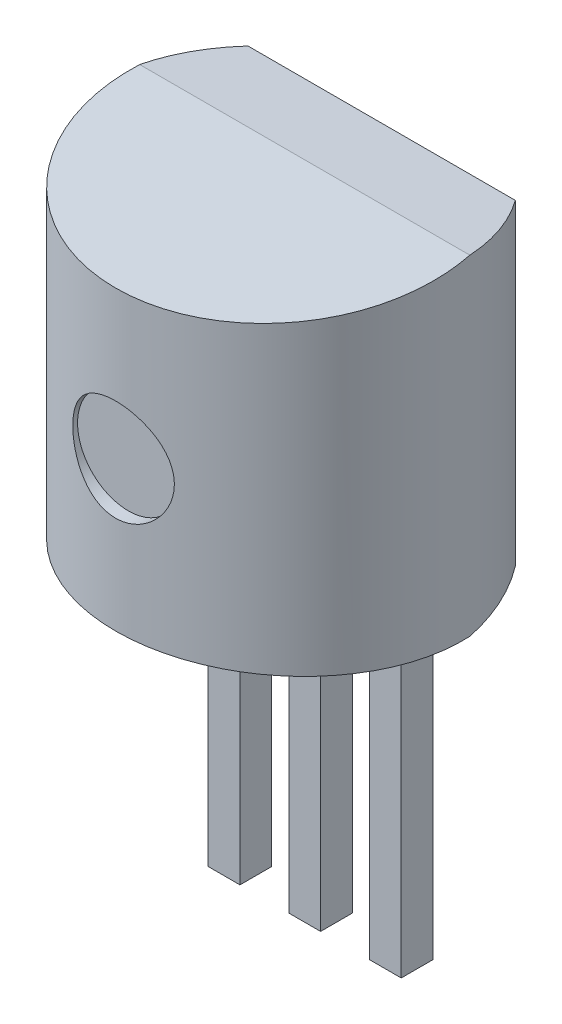
SolidWorks part; units mm, degrees
ref_plane "Front Plane" through (0, 0, 0) normal (0, 0, 1) x (1, 0, 0)
ref_plane "Top Plane" through (0, 0, 0) normal (0, 1, 0) x (1, 0, 0)
ref_plane "Right Plane" through (0, 0, 0) normal (1, 0, 0) x (0, 0, -1)
sketch "Sketch2" plane through (0, 0, 0) normal (0, 1, 0) x (1, 0, 0)
  line L0 (-2.6, 0) -> (2.6, 0) construction
  line L1 (-2.1054, 1.212) -> (2.1054, 1.212)
  line L2 (0, 0) -> (0, 1.212) construction
  arc A0 (-2.1054, 1.212) -> (2.1054, 1.212) centre (0, -0.354) ccw
  point P3 (0, 0)
  dimension "D1" = 4.19
  dimension "D2" = 5.2
  dimension "D3" = 2.27
extrude "Boss-Extrude1" add sketch "Sketch2" along normal mid plane 5.2
sketch "Sketch3" plane through (0, 2.6, 0) normal (0, 1, 0) x (1, 0, 0)
  line L0 (-2.6, 0) -> (2.6, 0) construction
  line L1 (-2.6, 0) -> (2.6, 0) construction
ref_plane "Plane1" through (0, 2.5803, -0.2257) normal (0, 0.9962, -0.0872) x (1, 0, 0)
ref_plane "Plane2" through (0, 2.5803, 0.2257) normal (0, 0.9962, 0.0872) x (1, 0, 0)
sketch "Sketch5" plane through (0, 2.5803, -0.2257) normal (0, 0.9962, -0.0872) x (1, 0, 0)
  line L1 (-4.9885, 2.0659) -> (6.8379, 2.0659)
  line L2 (-4.9885, 2.0659) -> (-4.9885, -3.5552)
  line L3 (-4.9885, -3.5552) -> (6.8379, -3.5552)
  line L4 (6.8379, 2.0659) -> (6.8379, -3.5552)
extrude "Cut-Extrude2" cut sketch "Sketch5" along normal through all
sketch "Sketch6" plane through (0, 2.5803, 0.2257) normal (0, 0.9962, 0.0872) x (1, 0, 0)
  line L1 (-5.588, 1.1618) -> (6.1027, 1.1618)
  line L2 (-5.588, 1.1618) -> (-5.588, -6.0928)
  line L3 (-5.588, -6.0928) -> (6.1027, -6.0928)
  line L4 (6.1027, 1.1618) -> (6.1027, -6.0928)
extrude "Cut-Extrude3" cut sketch "Sketch6" along normal blind 5.2
mirror "Mirror1" about plane through (0, 0, 0) normal (0, 1, 0) of "Cut-Extrude3", "Cut-Extrude2"
ref_plane "Plane3" through (0, -2.6, 0) normal (0, -1, 0) x (-1, 0, 0)
sketch "Sketch7" plane through (0, -2.6, 0) normal (0, -1, 0) x (-1, 0, 0)
  line L0 (-2.6, 0) -> (2.6, 0) construction
  line L1 (-1.52, 0) -> (-1.02, 0)
  line L2 (-1.52, 0) -> (-1.52, 0.5)
  line L3 (-1.52, 0.5) -> (-1.02, 0.5)
  line L4 (-1.02, 0) -> (-1.02, 0.5)
  line L5 (0, 0) -> (0, 0.5) construction
  line L6 (-0.25, 0) -> (0.25, 0)
  line L7 (-0.25, 0) -> (-0.25, 0.5)
  line L8 (-0.25, 0.5) -> (0.25, 0.5)
  line L9 (0.25, 0) -> (0.25, 0.5)
  line L10 (1.02, 0) -> (1.52, 0)
  line L11 (1.02, 0) -> (1.02, 0.5)
  line L12 (1.02, 0.5) -> (1.52, 0.5)
  line L13 (1.52, 0) -> (1.52, 0.5)
  line L14 (1.27, 0.5) -> (1.27, 0) construction
  line L15 (-1.27, 0.5) -> (-1.27, 0) construction
  dimension "D1" = 1.27
  dimension "D2" = 2.54
  dimension "D3" = 0.5
extrude "Boss-Extrude2" add sketch "Sketch7" along normal blind 12.7 and the other way up to body separate body
ref_plane "Plane4" through (0, 0, 2.978) normal (0, 0, 1) x (1, 0, 0)
sketch "Sketch8" plane through (0, 0, 2.978) normal (0, 0, 1) x (1, 0, 0)
  circle A0 centre (0, 0) radius 0.8
  dimension "D1" = 1.6
extrude "Cut-Extrude4" cut sketch "Sketch8" against normal blind 0.2
sketch "Sketch9" plane through (0, 0, -1.212) normal (0, 0, -1) x (-1, 0, 0)
  line L0 (-2.1054, 0.5896) -> (2.1054, 0.5896) construction
  line L1 (-2.1054, 2.494) -> (-2.1054, -2.494) construction
  text T0 "LM317LZ" font "Calibri" height in points 2
  point P8 (0, 0.5896)
split line "Split Line1"
sketch "Sketch10" plane through (0, 0, -1.212) normal (0, 0, -1) x (-1, 0, 0)
  line L0 (-2.6, -2.6) -> (-1.52, -2.6) construction
  line L1 (-2.8345, -7.8) -> (3.9349, -7.8)
  line L2 (-2.8345, -7.8) -> (-2.8345, -16.5787)
  line L3 (-2.8345, -16.5787) -> (3.9349, -16.5787)
  line L4 (3.9349, -7.8) -> (3.9349, -16.5787)
  dimension "D1" = 5.2
extrude "Cut-Extrude5" cut sketch "Sketch10" against normal through all
